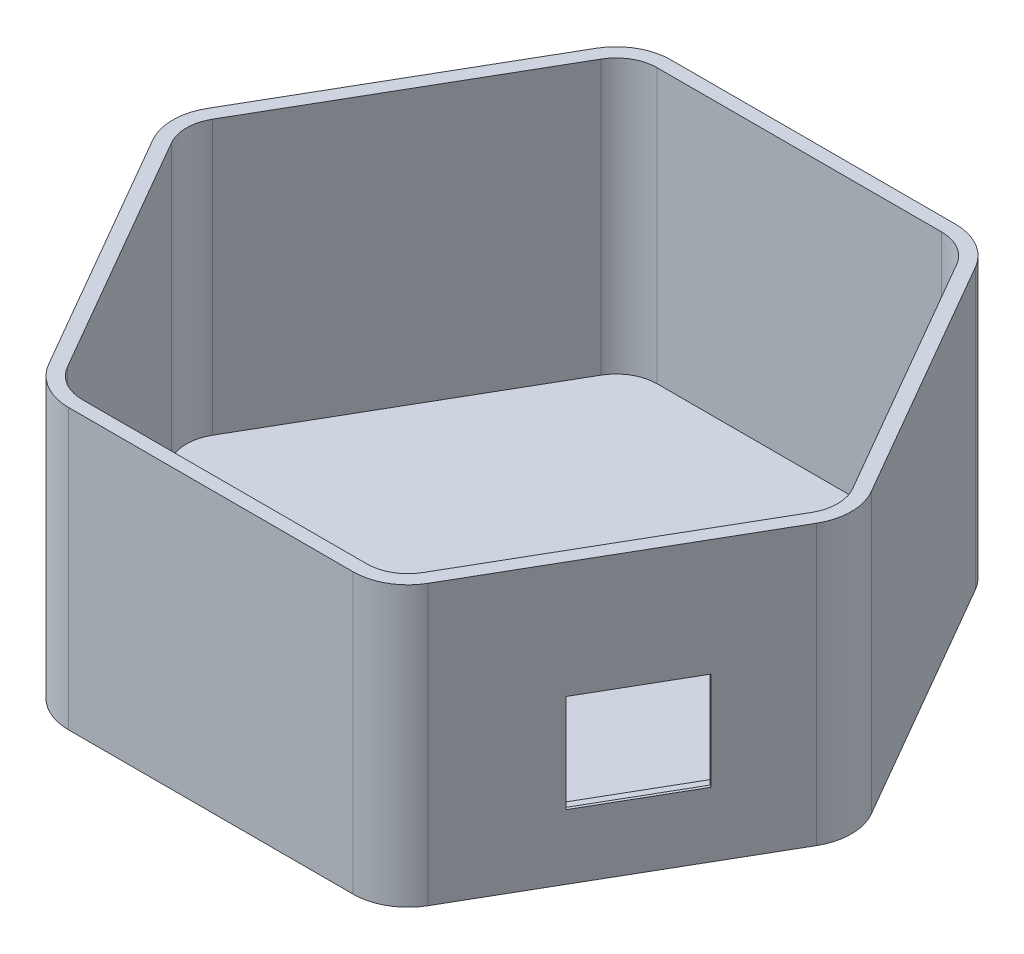
SolidWorks part; units mm, degrees
ref_plane "Front" through (0, 0, 0) normal (0, 0, 1) x (1, 0, 0)
ref_plane "Top" through (0, 0, 0) normal (0, 1, 0) x (1, 0, 0)
ref_plane "Right" through (0, 0, 0) normal (1, 0, 0) x (0, 0, -1)
sketch "Croquis1" plane through (0, 0, 0) normal (0, 1, 0) x (1, 0, 0)
  line L1 (-121.2436, -10) -> (-69.282, -100)
  line L2 (-51.9615, -110) -> (51.9615, -110)
  line L3 (69.282, -100) -> (121.2436, -10)
  line L4 (121.2436, 10) -> (69.282, 100)
  line L5 (51.9615, 110) -> (-51.9615, 110)
  line L6 (-69.282, 100) -> (-121.2436, 10)
  circle A0 centre (0, 0) radius 110 construction
  arc A1 (-69.282, 100) -> (-51.9615, 110) centre (-51.9615, 90) cw
  arc A2 (69.282, 100) -> (51.9615, 110) centre (51.9615, 90) ccw
  arc A3 (121.2436, -10) -> (121.2436, 10) centre (103.923, 0) ccw
  arc A4 (51.9615, -110) -> (69.282, -100) centre (51.9615, -90) ccw
  arc A5 (-69.282, -100) -> (-51.9615, -110) centre (-51.9615, -90) ccw
  arc A6 (-121.2436, -10) -> (-121.2436, 10) centre (-103.923, 0) cw
  dimension "D1" = 220
  dimension "D2" = 20
extrude "Saliente-Extruir1" add sketch "Croquis1" along normal blind 2
sketch "Croquis2" plane through (0, 2, 0) normal (0, 1, 0) x (1, 0, 0)
  line L6 (-64.9519, 97.5) -> (-116.9134, 7.5)
  line L7 (-116.9134, -7.5) -> (-64.9519, -97.5)
  line L8 (-51.9615, -105) -> (51.9615, -105)
  line L9 (64.9519, -97.5) -> (116.9134, -7.5)
  line L10 (116.9134, 7.5) -> (64.9519, 97.5)
  line L11 (51.9615, 105) -> (-51.9615, 105)
  line L12 (-69.282, 100) -> (-121.2436, 10)
  line L13 (-121.2436, -10) -> (-69.282, -100)
  line L14 (-51.9615, -110) -> (51.9615, -110)
  line L15 (69.282, -100) -> (121.2436, -10)
  line L16 (121.2436, 10) -> (69.282, 100)
  line L17 (51.9615, 110) -> (-51.9615, 110)
  line L18 (-69.282, 100) -> (-121.2436, 10)
  line L19 (-121.2436, -10) -> (-69.282, -100)
  line L20 (-51.9615, -110) -> (51.9615, -110)
  line L21 (69.282, -100) -> (121.2436, -10)
  line L22 (121.2436, 10) -> (69.282, 100)
  line L23 (51.9615, 110) -> (-51.9615, 110)
  arc A6 (-116.9134, 7.5) -> (-116.9134, -7.5) centre (-103.923, 0) ccw
  arc A7 (-64.9519, -97.5) -> (-51.9615, -105) centre (-51.9615, -90) ccw
  arc A8 (51.9615, -105) -> (64.9519, -97.5) centre (51.9615, -90) ccw
  arc A9 (116.9134, -7.5) -> (116.9134, 7.5) centre (103.923, 0) ccw
  arc A10 (64.9519, 97.5) -> (51.9615, 105) centre (51.9615, 90) ccw
  arc A11 (-51.9615, 105) -> (-64.9519, 97.5) centre (-51.9615, 90) ccw
  arc A12 (-51.9615, 110) -> (-69.282, 100) centre (-51.9615, 90) ccw
  arc A13 (-121.2436, 10) -> (-121.2436, -10) centre (-103.923, 0) ccw
  arc A14 (-69.282, -100) -> (-51.9615, -110) centre (-51.9615, -90) ccw
  arc A15 (51.9615, -110) -> (69.282, -100) centre (51.9615, -90) ccw
  arc A16 (121.2436, -10) -> (121.2436, 10) centre (103.923, 0) ccw
  arc A17 (69.282, 100) -> (51.9615, 110) centre (51.9615, 90) ccw
  arc A18 (-51.9615, 110) -> (-69.282, 100) centre (-51.9615, 90) ccw
  arc A19 (-121.2436, 10) -> (-121.2436, -10) centre (-103.923, 0) ccw
  arc A20 (-69.282, -100) -> (-51.9615, -110) centre (-51.9615, -90) ccw
  arc A21 (51.9615, -110) -> (69.282, -100) centre (51.9615, -90) ccw
  arc A22 (121.2436, -10) -> (121.2436, 10) centre (103.923, 0) ccw
  arc A23 (69.282, 100) -> (51.9615, 110) centre (51.9615, 90) ccw
  dimension "D1" = 0
  dimension "D2" = 5
extrude "Saliente-Extruir2" add sketch "Croquis2" along normal blind 100
sketch "Croquis3" plane through (90.9327, 0, 52.5) normal (-0.866, 0, -0.5) x (-0.5, 0, 0.866)
  line L1 (27.9238, 60.6352) -> (27.9238, 22.4352)
  line L2 (27.9238, 60.6352) -> (-30.7762, 60.6352)
  line L3 (-30.7762, 60.6352) -> (-30.7762, 22.4352)
  line L4 (27.9238, 22.4352) -> (-30.7762, 22.4352)
  line L5 (-23.7762, 59.4352) -> (15.0238, 59.4352)
  line L6 (-23.7762, 59.4352) -> (-23.7762, 23.6352)
  line L7 (-23.7762, 23.6352) -> (15.0238, 23.6352)
  line L8 (15.0238, 59.4352) -> (15.0238, 23.6352)
  circle A0 centre (24.9238, 57.6352) radius 1.5
  circle A1 centre (24.9238, 25.4352) radius 1.5
  circle A2 centre (-27.7762, 25.4352) radius 1.5
  circle A3 centre (-27.7762, 57.6352) radius 1.5
  dimension "D1" = 3
  dimension "D2" = 3
  dimension "D3" = 58.7
  dimension "D4" = 3
  dimension "D5" = 3
  dimension "D6" = 3
  dimension "D7" = 3
  dimension "D8" = 3
  dimension "D9" = 3
  dimension "D10" = 3
  dimension "D11" = 38.2
  dimension "D12" = 35.8
  dimension "D13" = 38.8
  dimension "D14" = 1.2
  dimension "D15" = 7
extrude "Cortar-Extruir1" cut sketch "Croquis3" against normal blind 1
sketch "Croquis4" plane through (90.9327, 0, 52.5) normal (-0.866, 0, -0.5) x (-0.5, 0, 0.866)
  line L4 (15.0238, 59.4352) -> (-23.7762, 59.4352)
  line L5 (-23.7762, 59.4352) -> (-23.7762, 23.6352)
  line L6 (-23.7762, 23.6352) -> (15.0238, 23.6352)
  line L7 (15.0238, 23.6352) -> (15.0238, 59.4352)
  line L8 (15.0238, 59.4352) -> (-23.7762, 59.4352)
  line L9 (-23.7762, 59.4352) -> (-23.7762, 23.6352)
  line L10 (-23.7762, 23.6352) -> (15.0238, 23.6352)
  line L11 (15.0238, 23.6352) -> (15.0238, 59.4352)
  dimension "D1" = 0
extrude "Cortar-Extruir2" cut sketch "Croquis4" against normal blind 12
sketch "Croquis5" plane through (91.7987, 0, 53) normal (-0.866, 0, -0.5) x (-0.5, 0, 0.866)
  line L4 (27.9238, 60.6352) -> (-30.7762, 60.6352)
  line L5 (-30.7762, 60.6352) -> (-30.7762, 22.4352)
  line L6 (-30.7762, 22.4352) -> (27.9238, 22.4352)
  line L7 (27.9238, 22.4352) -> (27.9238, 60.6352)
  line L8 (27.9238, 60.6352) -> (-30.7762, 60.6352)
  line L9 (-30.7762, 60.6352) -> (-30.7762, 22.4352)
  line L10 (-30.7762, 22.4352) -> (27.9238, 22.4352)
  line L11 (27.9238, 22.4352) -> (27.9238, 60.6352)
  circle A0 centre (24.9238, 25.4352) radius 1.5 construction
  circle A1 centre (24.9238, 57.6352) radius 1.5 construction
  circle A2 centre (-27.7762, 57.6352) radius 1.5 construction
  circle A3 centre (-27.7762, 25.4352) radius 1.5 construction
  circle A4 centre (24.9238, 25.4352) radius 1.5
  circle A5 centre (24.9238, 57.6352) radius 1.5
  circle A6 centre (-27.7762, 57.6352) radius 1.5
  circle A7 centre (-27.7762, 25.4352) radius 1.5
  dimension "D1" = 0
extrude "Cortar-Extruir3" cut sketch "Croquis5" against normal blind 3
sketch "Croquis6" plane through (94.3968, 0, 54.5) normal (-0.866, 0, -0.5) x (-0.5, 0, 0.866)
  line L0 (-28.444, 58.9783) -> (-27.1084, 56.292) construction
  line L1 (-30.7762, 60.6352) -> (-25.7762, 60.6352)
  line L2 (-30.7762, 60.6352) -> (-30.7762, 55.6352)
  line L3 (-30.7762, 55.6352) -> (-26.7762, 55.6352)
  line L4 (-25.7762, 60.6352) -> (-25.7762, 56.6352)
  line L5 (-30.7762, 22.4352) -> (-25.7762, 22.4352)
  line L6 (-30.7762, 22.4352) -> (-30.7762, 27.4352)
  line L7 (-30.7762, 27.4352) -> (-26.7762, 27.4352)
  line L8 (-25.7762, 22.4352) -> (-25.7762, 26.4352)
  line L9 (27.9238, 22.4352) -> (22.9238, 22.4352)
  line L10 (27.9238, 22.4352) -> (27.9238, 27.4352)
  line L11 (27.9238, 27.4352) -> (23.9238, 27.4352)
  line L12 (22.9238, 22.4352) -> (22.9238, 26.4352)
  line L13 (27.9238, 60.6352) -> (22.9238, 60.6352)
  line L14 (27.9238, 60.6352) -> (27.9238, 55.6352)
  line L15 (27.9238, 55.6352) -> (23.9238, 55.6352)
  line L16 (22.9238, 60.6352) -> (22.9238, 56.6352)
  circle A0 centre (-27.7762, 57.6352) radius 1.5 construction
  circle A1 centre (-27.7762, 57.6352) radius 1.5 construction
  circle A2 centre (-27.7762, 25.4352) radius 1
  circle A3 centre (-27.7762, 57.6352) radius 1
  circle A4 centre (24.9238, 57.6352) radius 1
  circle A5 centre (24.9238, 25.4352) radius 1
  arc A6 (-26.7762, 55.6352) -> (-25.7762, 56.6352) centre (-26.7762, 56.6352) ccw
  arc A7 (-25.7762, 26.4352) -> (-26.7762, 27.4352) centre (-26.7762, 26.4352) ccw
  arc A8 (22.9238, 26.4352) -> (23.9238, 27.4352) centre (23.9238, 26.4352) cw
  arc A9 (23.9238, 55.6352) -> (22.9238, 56.6352) centre (23.9238, 56.6352) cw
  point P39 (-25.7762, 55.6352)
  dimension "D1" = 5
  dimension "D9" = 1
  dimension "D2" = 5
  dimension "D3" = 5
  dimension "D4" = 5
  dimension "D5" = 5
  dimension "D6" = 5
  dimension "D7" = 5
  dimension "D8" = 5
extrude "Saliente-Extruir3" add sketch "Croquis6" along normal blind 3.4
sketch "Croquis8" plane through (90.9327, 0, 52.5) normal (-0.866, 0, -0.5) x (-0.5, 0, 0.866)
  circle A0 centre (-27.7762, 57.6352) radius 1
  circle A1 centre (-27.7762, 25.4352) radius 1
  circle A2 centre (24.9238, 25.4352) radius 1
  circle A3 centre (24.9238, 57.6352) radius 1
extrude "Cortar-Extruir5" cut sketch "Croquis8" against normal up to surface (4 mm away) up to face at (96.5849, 41.5352, 50.7101)
sketch "Croquis10" plane through (90.9327, 0, 52.5) normal (-0.866, 0, -0.5) x (-0.5, 0, 0.866)
  line L0 (27.9238, 60.6352) -> (-30.7762, 60.6352) construction
  line L1 (27.9238, 60.6352) -> (-30.7762, 60.6352)
  line L2 (-30.7762, 60.6352) -> (-30.7762, 22.4352) construction
  line L3 (-30.7762, 55.6352) -> (-30.7762, 27.4352) construction
  line L4 (-30.7762, 60.6352) -> (-30.7762, 22.4352)
  line L5 (-30.7762, 55.6352) -> (-30.7762, 27.4352)
  line L6 (-30.7762, 22.4352) -> (27.9238, 22.4352) construction
  line L7 (-30.7762, 22.4352) -> (27.9238, 22.4352)
  line L8 (27.9238, 22.4352) -> (27.9238, 60.6352) construction
  line L9 (27.9238, 22.4352) -> (27.9238, 60.6352)
  line M1 (-30.7762, 60.6352) -> (27.9238, 60.6352)
  line M2 (27.9238, 60.6352) -> (27.9238, 22.4352)
  line M3 (27.9238, 22.4352) -> (-30.7762, 22.4352)
  line M4 (-30.7762, 22.4352) -> (-30.7762, 60.6352)
extrude "Cortar-Extruir6" cut sketch "Croquis10" against normal up to surface (0.6 mm away) contours L4 M1 M4 M3 M2 up to face at (104.5904, 57.6352, 30.0442)
